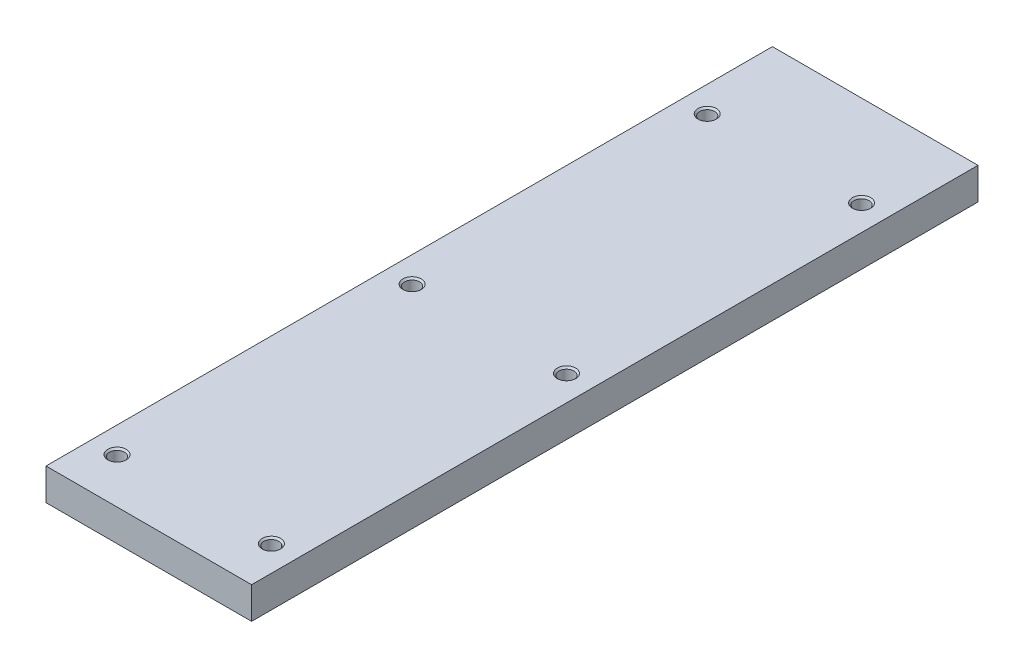
SolidWorks part; units mm, degrees
material "6063-T6"
ref_plane "Plan de face" through (0, 0, 0) normal (0, 0, 1) x (1, 0, 0)
ref_plane "Plan de dessus" through (0, 0, 0) normal (0, 1, 0) x (1, 0, 0)
ref_plane "Plan de droite" through (0, 0, 0) normal (1, 0, 0) x (0, 0, -1)
sketch "Esquisse1" plane through (0, 0, 0) normal (0, 0, 1) x (1, 0, 0)
  line L0 (17.144, -5.97) -> (-28.144, -5.97)
  line L1 (-5.5, -9.47) -> (17.144, -9.47) construction
  line L4 (-28.144, -12.97) -> (17.144, -12.97)
  line L6 (-28.144, -5.97) -> (-28.144, -12.97)
  line L8 (17.144, -5.97) -> (17.144, -12.97)
  circle A0 centre (-5.5, -77.47) radius 75 construction
  dimension "D1" = 7
extrude "Boss.-Extru.1" add sketch "Esquisse1" along a picked direction on the side of the normal blind 160 contours L4 L8 L0 L6
hole_wizard "Trou taraudé M41" positions "Esquisse2" profile "Esquisse3" tap size "M4" standard "DIN" end condition through all
sketch "Esquisse2" plane through (0.3548, -5.97, 0) normal (0, 1, 0) x (1, 0, 0)
  point P0 (-22.8548, -20)
  point P2 (-22.8548, -85)
  point P4 (-22.8548, -150)
  point P12 (11.1452, -150)
  point P15 (11.1452, -85)
  point P18 (11.1452, -20)
sketch "Esquisse3" plane through (-22.5, -5.97, 20) normal (1, 0, 0) x (0, 0, 1)
  line L0 (0, 0) -> (0, 7)
  line L1 (0, 7) -> (1.65, 7)
  line L2 (1.65, 7) -> (1.65, 0.375)
  line L3 (1.65, 0.375) -> (2.025, 0)
  line L5 (2.025, 0) -> (0, 0)
  line L6 (-1.65, 0.375) -> (-2.025, 0) construction
  line L11 (0, -6.35) -> (0, 107.95) construction
  dimension "Diamètre du trou pour taraudage jusqu'au prochain" = 3.3
  dimension "Profondeur du trou pour taraudage jusqu'au prochain" = 7
  dimension "Diamètre du fraisage entrant" = 4.05
  dimension "Angle du fraisage entrant" = 90
cosmetic thread "Filetage de perçage1" parameters "D2"=4
cosmetic thread "Filetage de perçage2" parameters "D2"=4
cosmetic thread "Filetage de perçage3" parameters "D2"=4
cosmetic thread "Filetage de perçage8" parameters "D2"=4
cosmetic thread "Filetage de perçage9" parameters "D2"=4
cosmetic thread "Filetage de perçage10" parameters "D2"=4
hole_wizard "Trou taraudé M53" positions "Esquisse6" profile "Esquisse8" tap size "M5" standard "DIN"
sketch "Esquisse6" plane through (0, 0, 0) normal (0, 0, -1) x (-1, 0, 0)
  line L3 (5.5, -77.47) -> (5.5, -2.47) construction
  line L4 (5.5, -5.97) -> (5.5, -9.47) construction
  line L5 (-17.144, -5.97) -> (28.144, -5.97) construction
  line L6 (5.5, -9.47) -> (5.5, -12.97) construction
  line L7 (28.144, -12.97) -> (-17.144, -12.97) construction
  point P0 (5.5, -9.47)
sketch "Esquisse8" plane through (-5.5, -9.47, 0) normal (1, 0, 0) x (0, 1, 0)
  line L0 (0, 0) -> (0, 51.2618)
  line L1 (0, 51.2618) -> (2.1, 50)
  line L2 (2.1, 50) -> (2.1, 0.425)
  line L3 (2.1, 0.425) -> (2.525, 0)
  line L5 (2.525, 0) -> (0, 0)
  line L6 (-2.1, 0.425) -> (-2.525, 0) construction
  line L10 (0, 51.2618) -> (-2.1, 50) construction
  line L11 (0, -6.35) -> (0, 107.95) construction
  dimension "Diamètre du trou pour taraudage" = 4.2
  dimension "Profondeur du trou pour taraudage" = 50
  dimension "Diamètre du fraisage entrant" = 5.05
  dimension "Angle du fraisage entrant" = 90
  dimension "Angle de pointe" = 118
cosmetic thread "Filetage de perçage7" parameters "D1"=0, "D2"=5.2
